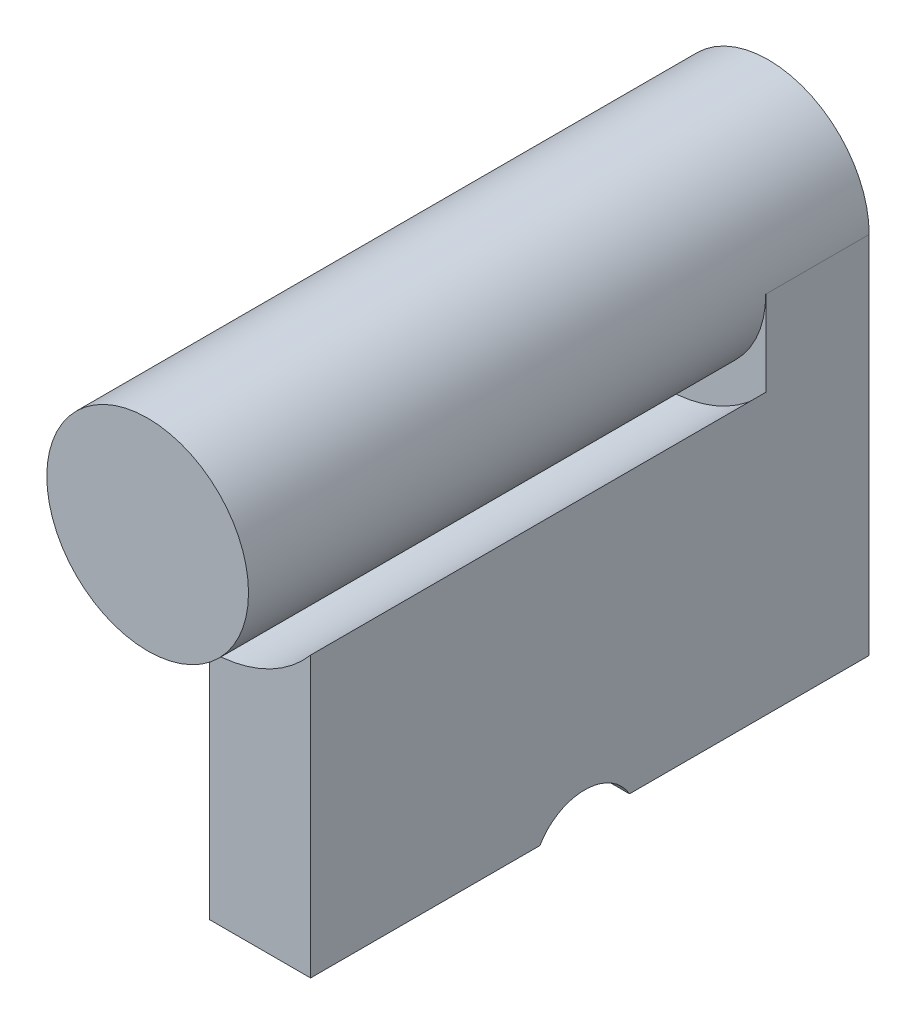
SolidWorks part; units mm, degrees
ref_plane "정면" through (0, 0, 0) normal (0, 0, 1) x (1, 0, 0)
ref_plane "윗면" through (0, 0, 0) normal (0, 1, 0) x (1, 0, 0)
ref_plane "우측면" through (0, 0, 0) normal (1, 0, 0) x (0, 0, -1)
sketch "스케치1" plane through (0, 0, 0) normal (0, 0, 1) x (1, 0, 0)
  circle A0 centre (0, 0) radius 1.95
  dimension "D1" = 3.9
extrude "보스-돌출1" add sketch "스케치1" along normal blind 12
sketch "스케치4" plane through (0, 0, 0) normal (1, 0, 0) x (0, 0, -1)
  line L5 (-2, 1.95) -> (0, 1.95)
  line L6 (-2, 1.95) -> (-2, -7.05)
  line L7 (-2, -7.05) -> (0, -7.05)
  line L8 (0, 1.95) -> (0, -7.05)
  line L9 (-2, 1.95) -> (0, -7.05) construction
  line L10 (-2, -7.05) -> (0, 1.95) construction
  point P0 (-1, -2.55)
  dimension "D1" = 2
  dimension "D2" = 9
extrude "보스-돌출2" add sketch "스케치4" along normal blind 1.95
sketch "스케치8" plane through (0, 0, 2) normal (0, 0, 1) x (1, 0, 0)
  line L0 (0, -1.95) -> (0, -7.05)
  line L1 (0, -7.05) -> (1.95, -7.05)
  line L2 (1.95, -7.05) -> (1.95, -1.6432)
  line L3 (0, -2.55) -> (0, -7.05)
  line L4 (1.95, -7.05) -> (1.95, -1.6432)
  line L5 (1.95, 0) -> (1.95, -7.05) construction
  line L6 (0, -1.95) -> (0, -7.05) construction
  circle A0 centre (0, 0) radius 1.95 construction
  circle A2 centre (0, 0) radius 1.95
  circle A3 centre (0, 0) radius 1.95
  circle A5 centre (0, 0) radius 2.55
  dimension "D2" = 5.1
  dimension "D1" = 0
extrude "보스-돌출4" add sketch "스케치8" along normal blind 8.8
sketch "스케치9" plane through (0, 0, 0) normal (-1, 0, 0) x (0, 0, 1)
  line L1 (12, -1.95) -> (12, 1.95) construction
  line L6 (10.8, -7.05) -> (0, -7.05) construction
  circle A0 centre (5.5, -7.55) radius 1
  dimension "D1" = 2
  dimension "D2" = 6.5
  dimension "D3" = 0.5
extrude "컷-돌출2" cut sketch "스케치9" against normal blind 17
sketch "스케치12" plane through (0, 0, 2) normal (0, 0, 1) x (1, 0, 0)
  line L0 (0, 1.95) -> (1.95, 1.95)
  line L1 (1.95, 1.95) -> (1.95, 0)
  circle A1 centre (0, 0) radius 1.95
  line M7 (1.95, 1.95) -> (0, 1.95)
  arc M8 (0, 1.95) -> (1.95, 0) centre (0, 0) cw
  line M9 (1.95, 0) -> (1.95, 1.95)
sketch "스케치13" plane through (0, 0, 0) normal (-1, 0, 0) x (0, 0, 1)
  line L0 (10.8, -7.05) -> (6.366, -7.05) construction
  line L2 (0, -7.05) -> (0, -1.95) construction
  circle A0 centre (5.505, -7.55) radius 1.375
  dimension "D1" = 0.5
  dimension "D2" = 2.75
  dimension "D3" = 5.505
extrude "컷-돌출6" cut sketch "스케치13" against normal blind 1
extrude "컷-돌출7" cut sketch "스케치12" against normal through all contours M9 M7 M8
scale "축척1" bodies to scale 111 scale about origin uniform scaling yes scale factor 2
equation "\"15.9.00mm\"= 15.9"
equation "\"D1\" = 1.50mm"
